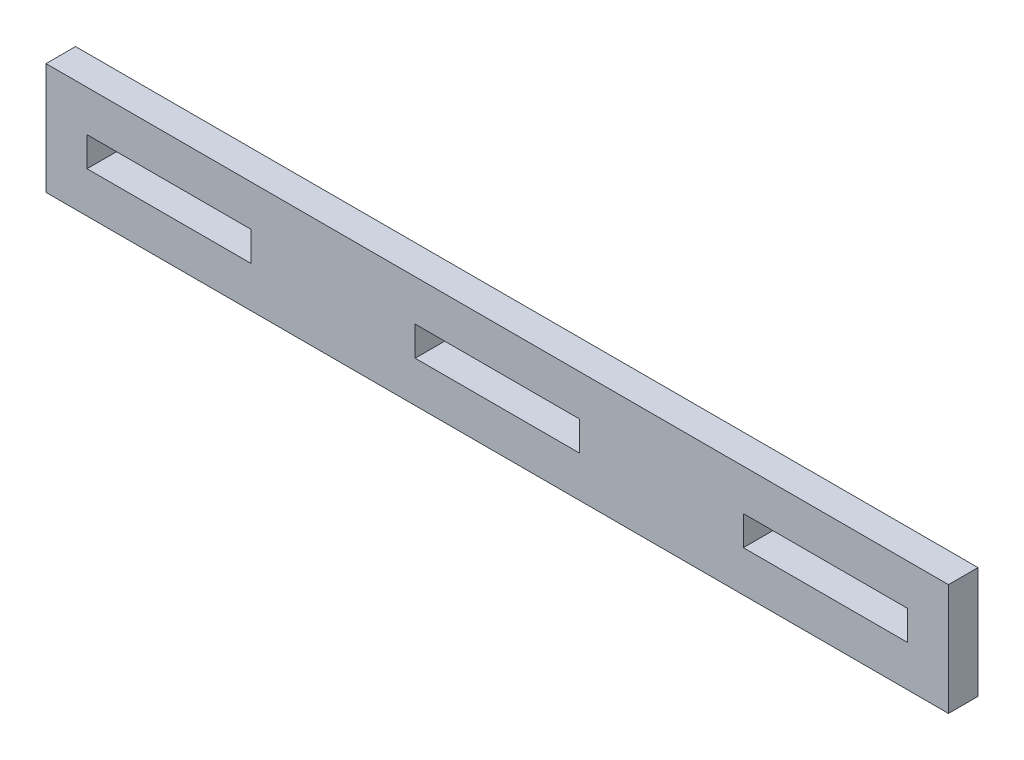
SolidWorks part; units mm, degrees
ref_plane "Front Plane" through (0, 0, 0) normal (0, 0, 1) x (1, 0, 0)
ref_plane "Top Plane" through (0, 0, 0) normal (0, 1, 0) x (1, 0, 0)
ref_plane "Right Plane" through (0, 0, 0) normal (1, 0, 0) x (0, 0, -1)
sketch "Sketch2" plane through (0, 0, 0) normal (0, 0, 1) x (1, 0, 0)
  line L1 (0, 0) -> (139.7, 0)
  line L2 (0, 0) -> (0, 17.272)
  line L3 (0, 17.272) -> (139.7, 17.272)
  line L4 (139.7, 0) -> (139.7, 17.272)
  dimension "D1" = 139.7
  dimension "D2" = 17.272
extrude "Boss-Extrude1" add sketch "Sketch2" along normal blind 4.572
sketch "Sketch3" plane through (0, 0, 4.572) normal (0, 0, 1) x (1, 0, 0)
  line L0 (139.7, 0) -> (139.7, 17.272) construction
  line L1 (107.95, 10.922) -> (133.35, 10.922)
  line L2 (107.95, 10.922) -> (107.95, 6.35)
  line L3 (107.95, 6.35) -> (133.35, 6.35)
  line L4 (133.35, 10.922) -> (133.35, 6.35)
  line L5 (139.7, 17.272) -> (0, 17.272) construction
  line L7 (82.55, 10.922) -> (57.15, 10.922)
  line L8 (82.55, 10.922) -> (82.55, 6.35)
  line L9 (82.55, 6.35) -> (57.15, 6.35)
  line L10 (57.15, 10.922) -> (57.15, 6.35)
  line L11 (31.75, 10.922) -> (6.35, 10.922)
  line L12 (31.75, 10.922) -> (31.75, 6.35)
  line L13 (31.75, 6.35) -> (6.35, 6.35)
  line L14 (6.35, 10.922) -> (6.35, 6.35)
  dimension "D1" = 4.572
  dimension "D2" = 25.4
  dimension "D3" = 6.35
  dimension "D4" = 6.35
  dimension "D5" = 4.572
  dimension "D6" = 4.572
  dimension "D7" = 25.4
  dimension "D8" = 25.4
  dimension "D9" = 25.4
  dimension "D10" = 25.4
extrude "Cut-Extrude1" cut sketch "Sketch3" against normal blind 4.572
